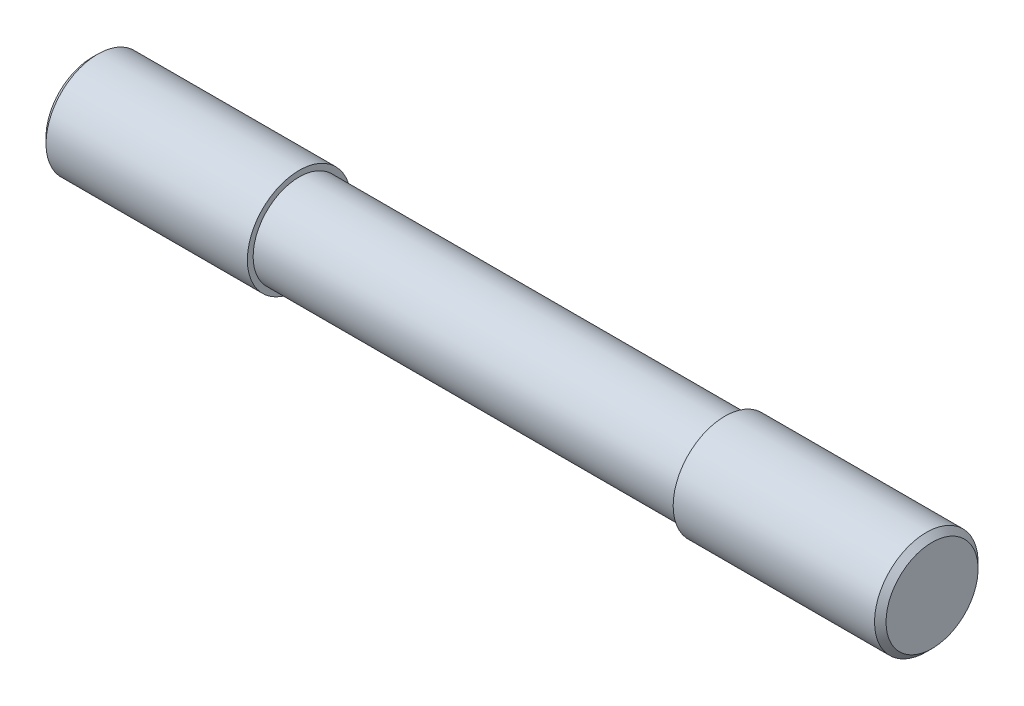
SolidWorks part; units mm, degrees
material "Alloy Steel"
ref_plane "Front Plane" through (0, 0, 0) normal (0, 0, 1) x (1, 0, 0)
ref_plane "Top Plane" through (0, 0, 0) normal (0, 1, 0) x (1, 0, 0)
ref_plane "Right Plane" through (0, 0, 0) normal (1, 0, 0) x (0, 0, -1)
sketch "Sketch1" plane through (0, 0, 0) normal (0, 1, 0) x (1, 0, 0)
  line L0 (-60.5842, 0) -> (62.0097, 0) construction
  line L1 (182.5, 20) -> (182.5, 5) construction
  line L2 (365, 0) -> (365, 22.5)
  line L3 (365, 22.5) -> (275, 22.5)
  line L4 (275, 22.5) -> (275, 20)
  line L5 (275, 20) -> (90, 20)
  line L6 (90, 22.5) -> (90, 20)
  line L7 (0, 22.5) -> (90, 22.5)
  line L8 (0, 0) -> (0, 22.5)
  line L9 (0, 0) -> (365, 0)
  point P11 (182.5, 20)
  dimension "D1" = 90
  dimension "D2" = 22.5
  dimension "D3" = 365
  dimension "D4" = 92.5
  dimension "D5" = 2.5
revolve "Revolve1" add sketch "Sketch1" angle 360 about L0
chamfer "Chamfer1" distance 2.5 angle 45 2 edges at (0, 0, 22.5) (365, 0, 22.5)
